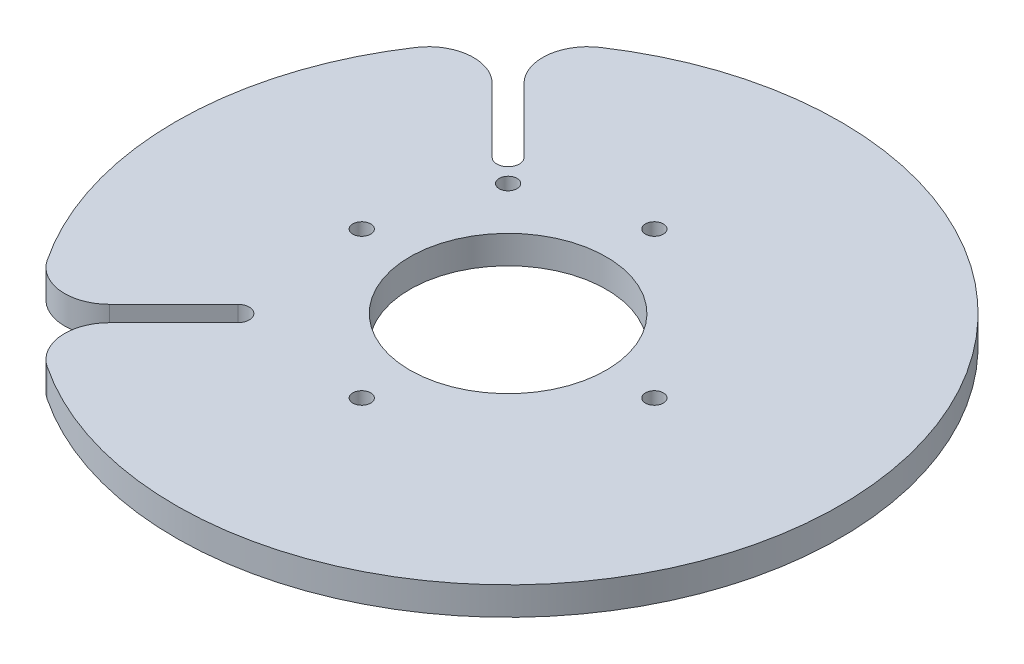
SolidWorks part; units mm, degrees
material "Acrylic (Medium-high impact)"
ref_plane "Front" through (0, 0, 0) normal (0, 0, 1) x (1, 0, 0)
ref_plane "Top" through (0, 0, 0) normal (0, 1, 0) x (1, 0, 0)
ref_plane "Right" through (0, 0, 0) normal (1, 0, 0) x (0, 0, -1)
sketch "Sketch1" plane through (0, 0, 0) normal (0, 1, 0) x (1, 0, 0)
  circle A0 centre (0, 0) radius 75
  dimension "D1" = 150
extrude "Boss-Extrude1" add sketch "Sketch1" along normal blind 6.35
sketch "Sketch45" plane through (0, 6.35, 0) normal (0, 1, 0) x (1, 0, 0)
  line L0 (-30.48, 30.48) -> (-53.0026, 53.0026) construction
  line L1 (-32.2761, 28.6839) -> (-54.7986, 51.2065)
  line L2 (-28.6839, 32.2761) -> (-51.2065, 54.7986)
  line L3 (-30.48, -30.48) -> (-53.0026, -53.0026) construction
  line L4 (-28.6839, -32.2761) -> (-51.2065, -54.7986)
  line L5 (-32.2761, -28.6839) -> (-54.7986, -51.2065)
  line L6 (0, 0) -> (75, 0) construction
  circle A0 centre (0, 0) radius 22.1615
  circle A1 centre (0, 0) radius 33.02 construction
  circle A2 centre (0, 33.02) radius 2.0193
  circle A3 centre (-33.02, 0) radius 2.0193
  circle A4 centre (0, -33.02) radius 2.0193
  circle A5 centre (33.02, 0) radius 2.0193
  circle A6 centre (-25.4, 25.4) radius 2.0193
  arc A7 (-32.2761, 28.6839) -> (-28.6839, 32.2761) centre (-30.48, 30.48) ccw
  arc A8 (-51.2065, 54.7986) -> (-54.7986, 51.2065) centre (-53.0026, 53.0026) ccw
  arc A9 (-28.6839, -32.2761) -> (-32.2761, -28.6839) centre (-30.48, -30.48) ccw
  arc A10 (-54.7986, -51.2065) -> (-51.2065, -54.7986) centre (-53.0026, -53.0026) ccw
  circle A12 centre (0, 0) radius 75 construction
  point P16 (-41.7413, 41.7413)
  point P21 (-41.7413, -41.7413)
  dimension "D1" = 44.323
  dimension "D3" = 4.0386
  dimension "D10" = 2.54
  dimension "D2" = 33.02
  dimension "D4" = 25.4
  dimension "D5" = 25.4
  dimension "D6" = 30.48
  dimension "D7" = 30.48
  dimension "D8" = 30.48
  dimension "D9" = 30.48
  dimension "D11" = 45
extrude "Cut-Extrude36" cut sketch "Sketch45" against normal through all
fillet "Fillet2" radius 10.16 4 edges at (-51.2065, 3.175, 54.7986) (-54.7986, 3.175, 51.2065) (-51.2065, 3.175, -54.7986) (-54.7986, 3.175, -51.2065)
